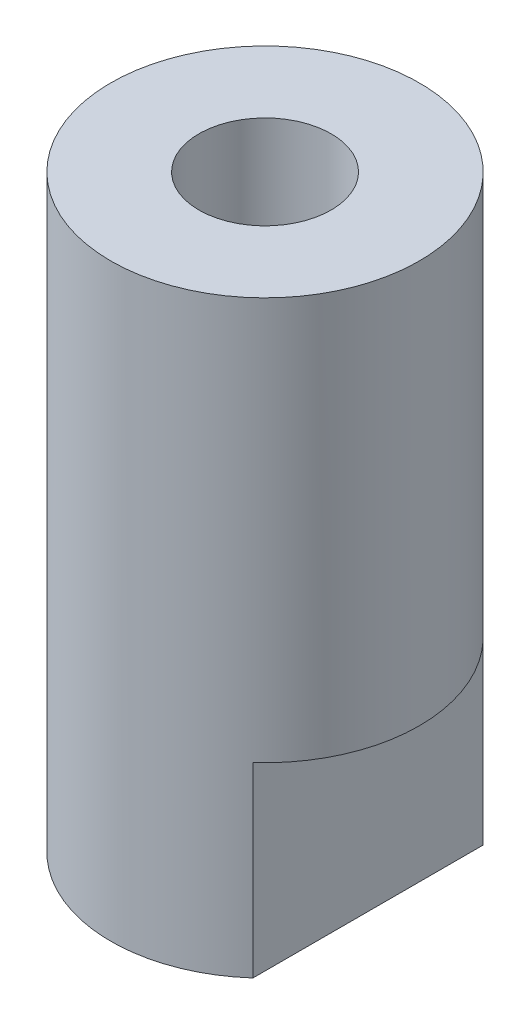
SolidWorks part; units mm, degrees
ref_plane "Front Plane" through (0, 0, 0) normal (0, 0, 1) x (1, 0, 0)
ref_plane "Top Plane" through (0, 0, 0) normal (0, 1, 0) x (1, 0, 0)
ref_plane "Right Plane" through (0, 0, 0) normal (1, 0, 0) x (0, 0, -1)
sketch "Sketch1" plane through (0, 0, 0) normal (0, 1, 0) x (1, 0, 0)
  circle A0 centre (0, 0) radius 10.5
  dimension "D1" = 21
extrude "Boss-Extrude1" add sketch "Sketch1" along normal blind 40.1
hole_wizard "M10x1.0 Tapped Hole1" positions "Sketch2" profile "Sketch3" tap size "M10x1.0" standard "ANSI Metric"
sketch "Sketch2" plane through (0, 40.1, 0) normal (0, 1, 0) x (1, 0, 0)
  point P0 (0, 0)
cosmetic thread "Hole Thread1" parameters "D1"=20, "D2"=10
sketch "Sketch3" plane through (0, 40.1, 0) normal (1, 0, 0) x (0, 0, 1)
  line L0 (0, 0) -> (0, 25.7039)
  line L1 (0, 25.7039) -> (4.5, 23)
  line L2 (4.5, 23) -> (4.5, 0)
  line L5 (4.5, 0) -> (0, 0)
  line L10 (0, 25.7039) -> (-4.5, 23) construction
  line L11 (0, -6.35) -> (0, 107.95) construction
  dimension "Tap Drill Dia." = 9
  dimension "Tap Drill Depth" = 23
  dimension "Drill Angle" = 118
hole_wizard "M8x1.0 Tapped Hole1" positions "Sketch4" profile "Sketch5" tap size "M8x1.0" standard "ANSI Metric"
sketch "Sketch4" plane through (0, 0, 0) normal (0, -1, 0) x (-1, 0, 0)
  point P0 (0, 0)
sketch "Sketch5" plane through (0, 0, 0) normal (1, 0, 0) x (0, 0, -1)
  line L0 (0, 0) -> (0, 21.103)
  line L1 (0, 21.103) -> (3.5, 19)
  line L2 (3.5, 19) -> (3.5, 0)
  line L5 (3.5, 0) -> (0, 0)
  line L10 (0, 21.103) -> (-3.5, 19) construction
  line L11 (0, -6.35) -> (0, 107.95) construction
  dimension "Tap Drill Dia." = 7
  dimension "Tap Drill Depth" = 19
  dimension "Drill Angle" = 118
cosmetic thread "Hole Thread2" parameters "D1"=16, "D2"=8
sketch "Sketch6" plane through (0, 0, 0) normal (0, 0, 1) x (1, 0, 0)
  line L0 (-10.5, 0) -> (-7, 0)
  line L1 (-10.5, 0) -> (-10.5, 12.7)
  line L2 (-7, 0) -> (-7, 12.7)
  line L3 (-10.5, 12.7) -> (-7, 12.7)
  line L4 (-10.5, 0) -> (10.5, 0) construction
  line L5 (10.5, 0) -> (7, 0)
  line L6 (10.5, 0) -> (10.5, 12.7)
  line L7 (7, 0) -> (7, 12.7)
  line L8 (10.5, 12.7) -> (7, 12.7)
  dimension "D1" = 12.7
  dimension "D2" = 14
extrude "Cut-Extrude1" cut sketch "Sketch6" against normal through all both and the other way through all
